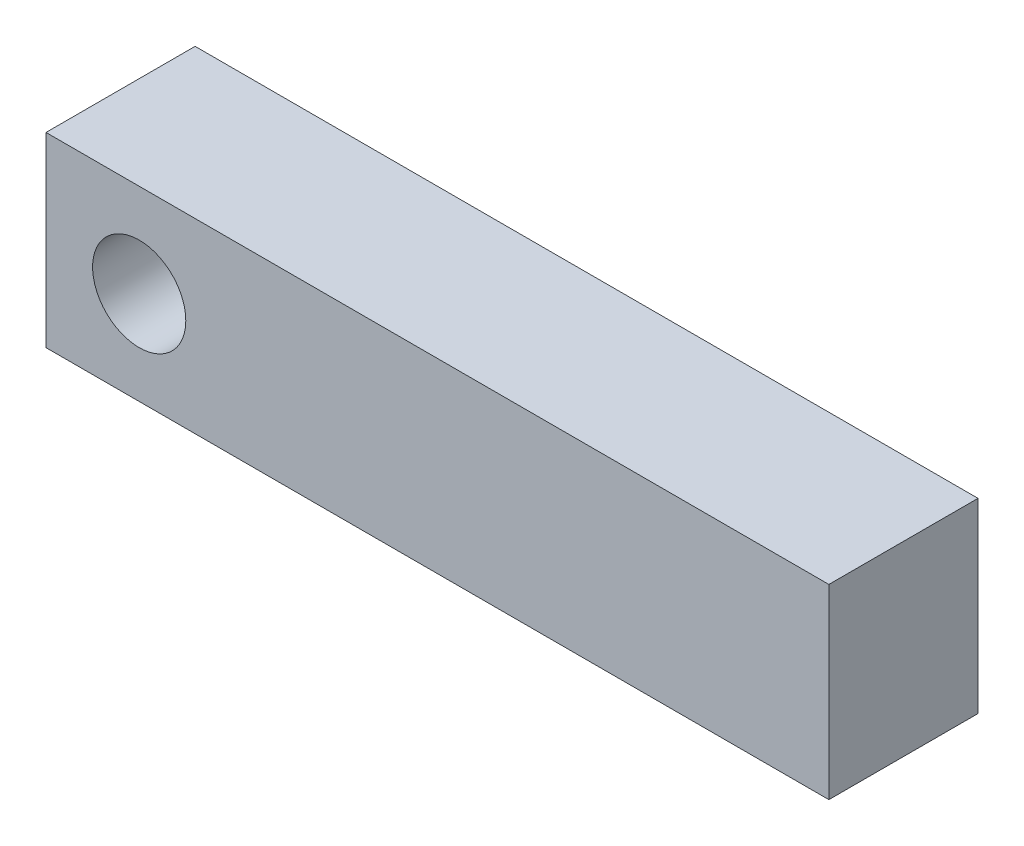
SolidWorks part; units mm, degrees
ref_plane "Alzado" through (0, 0, 0) normal (0, 0, 1) x (1, 0, 0)
ref_plane "Planta" through (0, 0, 0) normal (0, 1, 0) x (1, 0, 0)
ref_plane "Vista lateral" through (0, 0, 0) normal (1, 0, 0) x (0, 0, -1)
sketch "Croquis1" plane through (0, 0, 0) normal (0, 0, 1) x (1, 0, 0)
  line L0 (0, 0) -> (-25, 0) construction
  line L1 (-25, -25) -> (-25, 25)
  line L2 (-25, 25) -> (185, 25)
  line L3 (-25, -25) -> (185, -25)
  line L4 (185, 25) -> (185, -25)
  circle A0 centre (0, 0) radius 12.5
  dimension "D1" = 25
  dimension "D2" = 25
  dimension "D3" = 25
  dimension "D4" = 210
extrude "Saliente-Extruir1" add sketch "Croquis1" along normal blind 40
